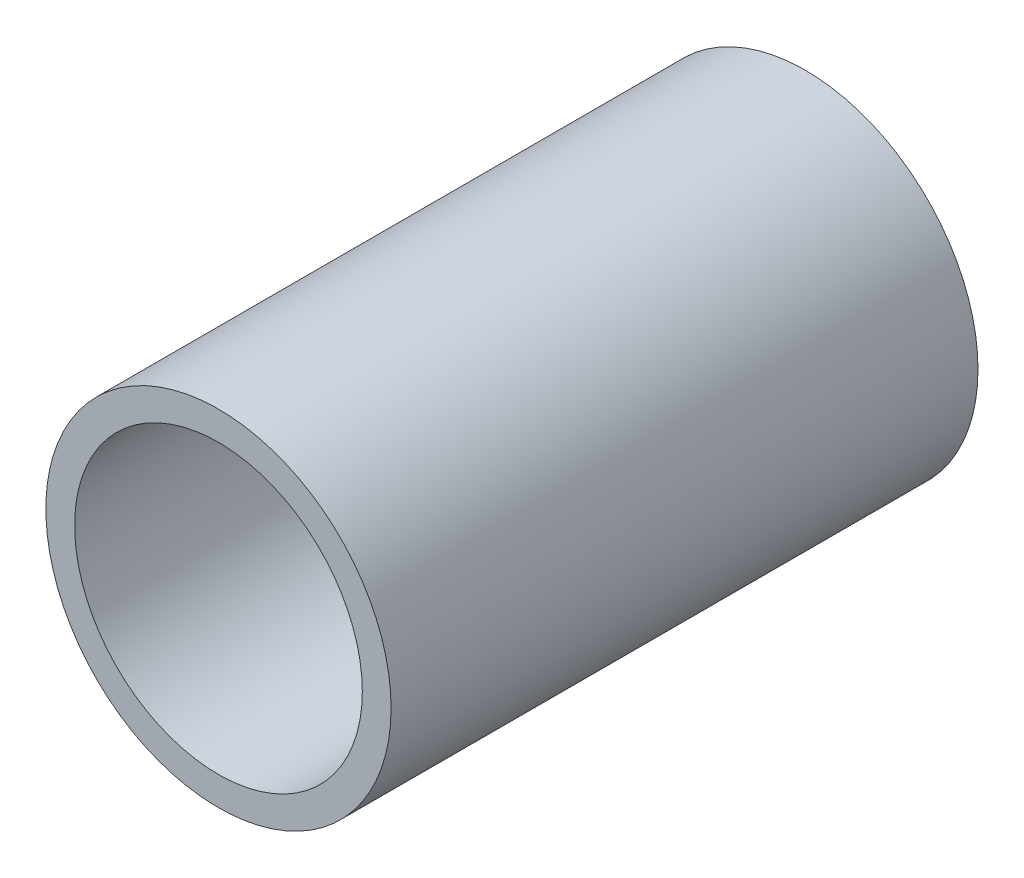
SolidWorks part; units mm, degrees
material "7075-T6 (SN)"
ref_plane "Alzado" through (0, 0, 0) normal (0, 0, 1) x (1, 0, 0)
ref_plane "Planta" through (0, 0, 0) normal (0, 1, 0) x (1, 0, 0)
ref_plane "Vista lateral" through (0, 0, 0) normal (1, 0, 0) x (0, 0, -1)
sketch "Croquis1" plane through (0, 0, 0) normal (0, 0, 1) x (1, 0, 0)
  circle A0 centre (0, 0) radius 15
  dimension "D1" = 30
extrude "Saliente-Extruir1" add sketch "Croquis1" along normal blind 51
sketch "Croquis2" plane through (0, 0, 51) normal (0, 0, 1) x (1, 0, 0)
  circle A0 centre (0, 0) radius 12.5
  dimension "D1" = 25
extrude "Cortar-Extruir1" cut sketch "Croquis2" against normal blind 47
